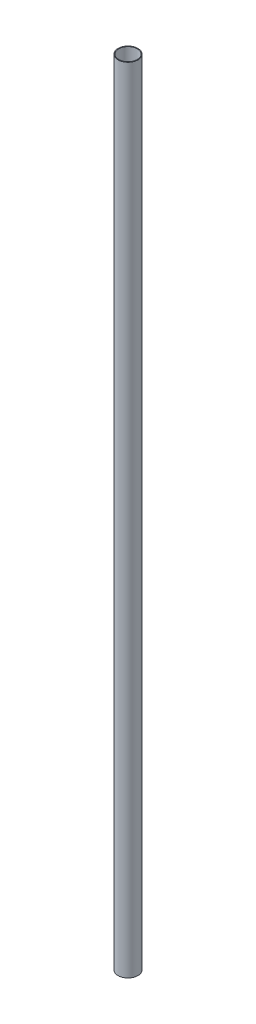
SolidWorks part; units mm, degrees
ref_plane "Front Plane" through (0, 0, 0) normal (0, 0, 1) x (1, 0, 0)
ref_plane "Top Plane" through (0, 0, 0) normal (0, 1, 0) x (1, 0, 0)
ref_plane "Right Plane" through (0, 0, 0) normal (1, 0, 0) x (0, 0, -1)
sketch "Sketch1" plane through (0, 0, 0) normal (0, 1, 0) x (1, 0, 0)
  circle A0 centre (0, 0) radius 3.25
  circle A1 centre (0, 0) radius 3.5
  dimension "D1" = 7
  dimension "D2" = 0.25
extrude "Boss-Extrude1" add sketch "Sketch1" along normal blind 278
equation "\"l2\"= 185"
equation "\"l1\"= 85"
equation "\"s1r\"= 2.14212rad"
equation "\"s2r\"= - 2rad"
equation "\"offset\"= 10mm"
equation "\"s1_len\"= 0.08255m"
equation "\"s2_len\"= 0.015m"
equation "\"s1_anchor_dist\"= \"offset\" + \"l1\" + \"s1_len\""
equation "\"s2_anchor_dist\"= \"offset\" + \"l1\" + \"s2_len\"'this was: = \"offset\" + \"l1\" + \"s2_len\""
equation "\"carbon_fiber_plate_thickness\"=6"
equation "\"motor_to_motor_spacing\"=55.5"
equation "\"D1@Boss-Extrude1\"=\"l1\"+\"l2\"+8mm"
